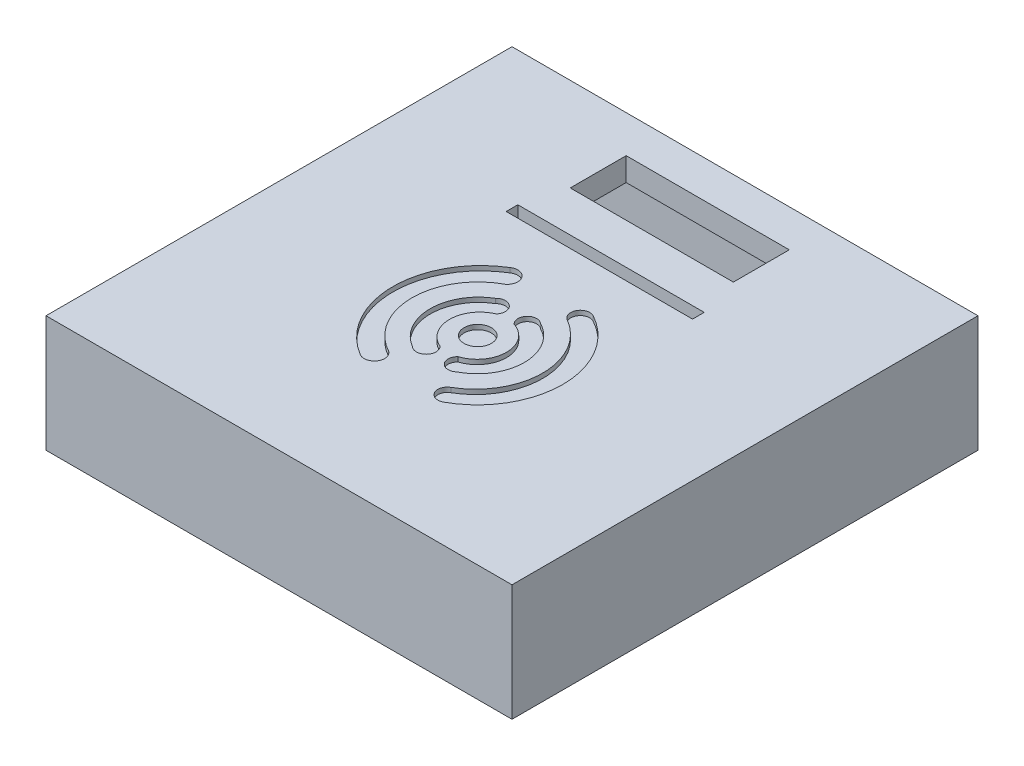
SolidWorks part; units mm, degrees
ref_plane "Plan de face" through (0, 0, 0) normal (0, 0, 1) x (1, 0, 0)
ref_plane "Plan de dessus" through (0, 0, 0) normal (0, 1, 0) x (1, 0, 0)
ref_plane "Plan de droite" through (0, 0, 0) normal (1, 0, 0) x (0, 0, -1)
sketch "Esquisse1" plane through (0, 0, 0) normal (0, 1, 0) x (1, 0, 0)
  line L1 (-100, 100) -> (100, 100)
  line L2 (-100, 100) -> (-100, -100)
  line L3 (-100, -100) -> (100, -100)
  line L4 (100, 100) -> (100, -100)
  point P7 (12.987, 89.6104)
  dimension "D1" = 100
  dimension "D2" = 100
  dimension "D3" = 100
  dimension "D4" = 100
extrude "Boss.-Extru.1" add sketch "Esquisse1" along normal blind 50
sketch "Esquisse2" plane through (0, 0, 0) normal (0, -1, 0) x (1, 0, 0)
  line L0 (-100, -100) -> (-100, 100) construction
  line L1 (-95, 95) -> (95, 95)
  line L2 (-95, 95) -> (-95, -95)
  line L3 (-95, -95) -> (95, -95)
  line L4 (95, 95) -> (95, -95)
  line L5 (-100, 100) -> (100, 100) construction
  line L6 (100, 100) -> (100, -100) construction
  line L7 (100, -100) -> (-100, -100) construction
  dimension "D1" = 5
  dimension "D2" = 5
  dimension "D3" = 5
  dimension "D4" = 5
extrude "Enlèv. mat.-Extru.1" cut sketch "Esquisse2" against normal blind 40
sketch "Esquisse3" plane through (0, 50, 0) normal (0, 1, 0) x (1, 0, 0)
  line L0 (100, -100) -> (100, 100) construction
  line L1 (-35, 84) -> (35, 84)
  line L2 (-35, 84) -> (-35, 60)
  line L3 (-35, 60) -> (35, 60)
  line L4 (35, 84) -> (35, 60)
  line L6 (100, 100) -> (-100, 100) construction
  dimension "D1" = 70
  dimension "D2" = 24
  dimension "D3" = 65
  dimension "D4" = 16
extrude "Enlèv. mat.-Extru.2" cut sketch "Esquisse3" against normal blind 10
sketch "Esquisse5" plane through (0, 40, 0) normal (0, -1, 0) x (1, 0, 0)
  line L0 (35, -60) -> (35, -84) construction
  line L1 (35, -81) -> (40, -81)
  line L2 (35, -81) -> (35, -63)
  line L3 (35, -63) -> (40, -63)
  line L4 (40, -81) -> (40, -63)
  line L5 (35, -84) -> (-35, -84) construction
  line L6 (-35, -60) -> (35, -60) construction
  line L8 (-35, -60) -> (-5, -60)
  line L9 (-35, -60) -> (-35, -46)
  line L10 (-35, -46) -> (-5, -46)
  line L11 (-5, -60) -> (-5, -46)
  dimension "D1" = 3
  dimension "D2" = 3
  dimension "D3" = 5
  dimension "D4" = 30
  dimension "D5" = 14
extrude "Enlèv. mat.-Extru.3" cut sketch "Esquisse5" against normal blind 6
sketch "Esquisse7" plane through (0, 40, 0) normal (0, -1, 0) x (1, 0, 0)
  line L0 (-35, -84) -> (-35, -46) construction
  line L1 (-35, -60) -> (-40, -60)
  line L2 (-35, -60) -> (-35, -46)
  line L3 (-35, -46) -> (-40, -46)
  line L4 (-40, -60) -> (-40, -46)
  line L5 (-5, -46) -> (-35, -46) construction
  dimension "D1" = 5
  dimension "D2" = 14
  dimension "D3" = 0
extrude "Enlèv. mat.-Extru.5" cut sketch "Esquisse7" against normal blind 6
sketch "Esquisse8" plane through (0, 40, 0) normal (0, -1, 0) x (1, 0, 0)
  line L4 (-95, 95) -> (-95, -95) construction
  line L5 (40, -42.5) -> (-40, -42.5)
  line L6 (40, -42.5) -> (40, -37.5)
  line L7 (40, -37.5) -> (-40, -37.5)
  line L8 (-40, -42.5) -> (-40, -37.5)
  line L11 (-95, -95) -> (95, -95) construction
  dimension "D1" = 80
  dimension "D2" = 55
  dimension "D3" = 5
  dimension "D4" = 52.5
extrude "Enlèv. mat.-Extru.6" cut sketch "Esquisse8" against normal blind 10
sketch "Esquisse9" plane through (0, 0, 95) normal (0, 0, -1) x (-1, 0, 0)
  line L0 (95, 40) -> (95, 0) construction
  line L1 (-95, 0) -> (95, 0)
  line L2 (-95, 0) -> (-95, 5)
  line L3 (-95, 5) -> (95, 5)
  line L4 (95, 0) -> (95, 5)
  dimension "D1" = 5
extrude "Boss.-Extru.2" add sketch "Esquisse9" along normal blind 75
sketch "Esquisse11" plane through (0, 40, 0) normal (0, -1, 0) x (1, 0, 0)
  line L0 (95, -95) -> (95, 95) construction
  line L1 (25, -4) -> (-25, -4)
  line L2 (25, -4) -> (25, 36)
  line L3 (25, 36) -> (-25, 36)
  line L4 (-25, -4) -> (-25, 36)
  line L6 (20, 1) -> (-20, 1)
  line L7 (20, 1) -> (20, 31)
  line L9 (20, 31) -> (-20, 31)
  line L10 (-20, 1) -> (-20, 31)
  line L12 (-95, 20) -> (95, 20) construction
  dimension "D1" = 40
  dimension "D2" = 50
  dimension "D3" = 70
  dimension "D4" = 5
  dimension "D5" = 5
  dimension "D6" = 5
  dimension "D7" = 5
  dimension "D8" = 16
extrude "Enlèv. mat.-Extru.9" cut sketch "Esquisse11" against normal blind 6
sketch "Esquisse12" plane through (0, 50, 0) normal (0, 1, 0) x (1, 0, 0)
  line L0 (32.6994, -218.1671) -> (351.6614, -186.6971) construction
  circle A0 centre (0, -14.7144) radius 5.8671
  arc A1 (3.6573, -2.7235) -> (3.6573, -26.765) centre (-0.2172, -14.7442) cw
  arc A2 (3.6573, -2.7235) -> (9.0219, 3.2372) centre (6.3396, 0.2569) cw
  arc A3 (9.0219, 3.2372) -> (9.0219, -32.7257) centre (-0.1604, -14.7442) cw
  arc A4 (3.6573, -26.765) -> (9.0219, -32.7257) centre (6.3396, -29.7454) ccw
  arc A5 (-4.0916, -2.7235) -> (-4.0916, -26.765) centre (0.9948, -14.7442) ccw
  arc A6 (-4.0916, -2.7235) -> (-10.0444, 2.9392) centre (-7.068, 0.1079) ccw
  arc A7 (-10.0444, 2.9392) -> (-10.0444, -32.7257) centre (0.5361, -14.8933) ccw
  arc A8 (-10.0444, -32.7257) -> (-4.0916, -26.765) centre (-7.068, -29.7454) ccw
  arc A9 (13.5918, 10.1914) -> (17.35, 17.4555) centre (15.4976, 13.8097) cw
  arc A10 (13.5918, -39.6799) -> (17.4025, -46.7863) centre (15.4708, -43.2472) ccw
  arc A11 (-13.2314, -39.6799) -> (-18.3974, -46.8146) centre (-15.8144, -43.2472) cw
  arc A12 (-13.2314, 10.1914) -> (-18.3974, 17.4559) centre (-15.8144, 13.8236) ccw
  arc A13 (-18.3974, 17.4559) -> (-18.3974, -46.8146) centre (1.2524, -14.6794) ccw
  arc A14 (-13.2314, 10.1914) -> (-13.2314, -39.6799) centre (0.1339, -14.7442) ccw
  arc A15 (13.5918, 10.1914) -> (13.5918, -39.6799) centre (-0.9457, -14.7442) cw
  arc A16 (17.35, 17.4555) -> (17.4025, -46.7863) centre (-0.1222, -14.6797) cw
extrude "Enlèv. mat.-Extru.10" cut sketch "Esquisse12" against normal blind 2
sketch "Esquisse13" plane through (-95, 0, 0) normal (1, 0, 0) x (0, 0, -1)
  line L1 (-20, 5) -> (-40, 5)
  line L2 (-20, 5) -> (-20, 15)
  line L3 (-20, 15) -> (-40, 15)
  line L4 (-40, 5) -> (-40, 15)
  dimension "D1" = 20
  dimension "D2" = 10
extrude "Enlèv. mat.-Extru.11" cut sketch "Esquisse13" against normal blind 5
